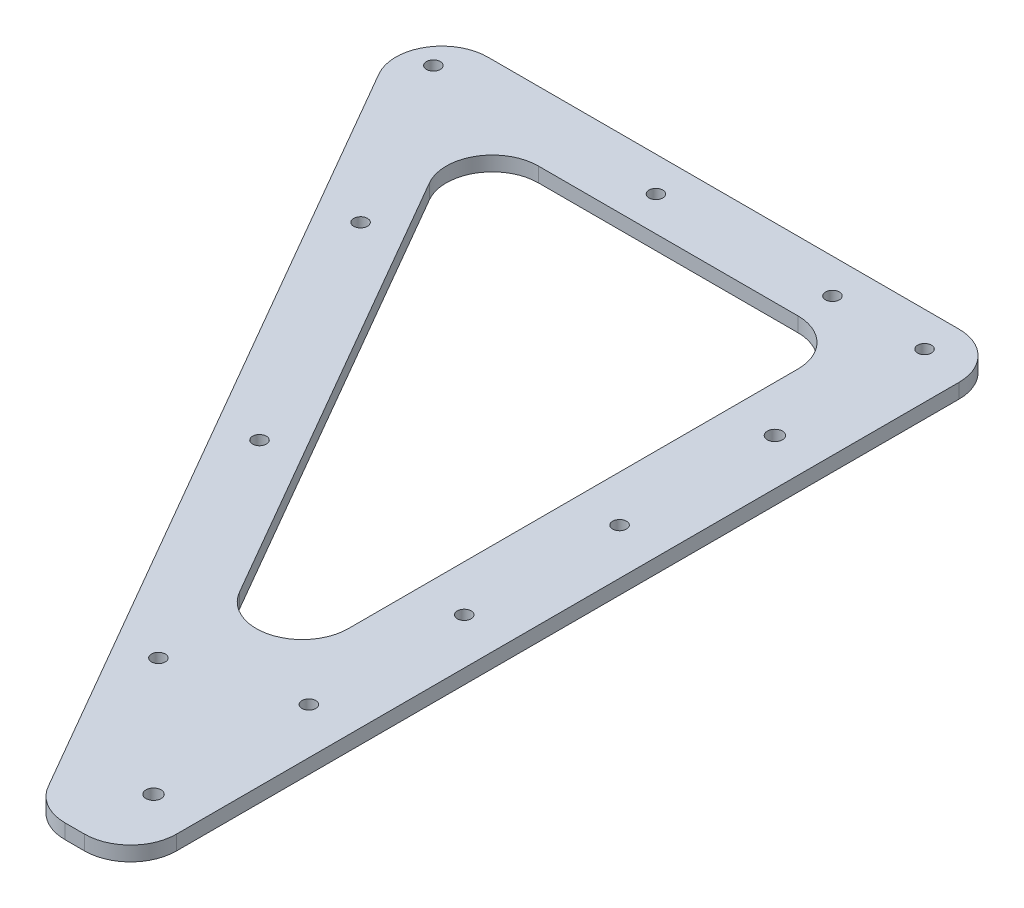
SolidWorks part; units mm, degrees
ref_plane "Front" through (0, 0, 0) normal (0, 0, 1) x (1, 0, 0)
ref_plane "Top" through (0, 0, 0) normal (0, 1, 0) x (1, 0, 0)
ref_plane "Right" through (0, 0, 0) normal (1, 0, 0) x (0, 0, -1)
sketch "Sketch1" plane through (0, 0, 0) normal (0, 1, 0) x (1, 0, 0)
  line L0 (-20, -190) -> (-129.6966, 0)
  line L1 (0, 0) -> (-20, 0)
  line L2 (0, 0) -> (0, -190)
  line L3 (0, -190) -> (-20, -190)
  line L4 (-20, 0) -> (-20, -190)
  line L5 (-129.6966, 0) -> (-20, 0)
  line L6 (-10, -190) -> (-10, -175)
  line L7 (-10, -175) -> (-10, -40)
  line L8 (-13.5048, -186.25) -> (-116.7062, -7.5)
  line L9 (-116.7062, -7.5) -> (-20, -7.5)
  line L10 (-7.0096, -182.5) -> (-103.7158, -15)
  line L11 (-103.7158, -15) -> (-20, -15)
  circle A0 centre (-10, -175) radius 1.65
  circle A1 centre (-10, -40) radius 1.65
  circle A2 centre (-116.7062, -7.5) radius 1.5
  circle A3 centre (-68.3531, -7.5) radius 1.5
  circle A5 centre (-10, -107.5) radius 1500
  circle A6 centre (-10, -7.5) radius 1.5
  circle A7 centre (-10, -107.5) radius 1.5
  circle A8 centre (-10, -141.25) radius 1.5
  circle A9 centre (-10, -73.75) radius 1.5
  circle A10 centre (-65.1055, -96.875) radius 1.5
  circle A11 centre (-95.1055, -44.9135) radius 1.5
  circle A12 centre (-35.1055, -148.8365) radius 1.5
  circle A13 centre (-30, -7.5) radius 1.5
  point P37 (0, 0)
  dimension "D6" = 7.5
  dimension "D7" = 33.75
  dimension "D10" = 60
  dimension "D1" = 20
  dimension "D2" = 190
  dimension "D3" = 109.6966
  dimension "D4" = 15
  dimension "D5" = 135
  dimension "D8" = 33.75
  dimension "D11" = 60
  dimension "D12" = 10
  dimension "D9" = 15
extrude "Boss-Extrude1" add sketch "Sketch1" along normal blind 3.175
fillet "Fillet1" radius 10 7 edges at (-20, 1.5875, 15) (-103.7158, 1.5875, 15) (-129.6966, 1.5875, 0) (0, 1.5875, 0) (0, 1.5875, 190) (-20, 1.5875, 190) (-20, 1.5875, 160)
